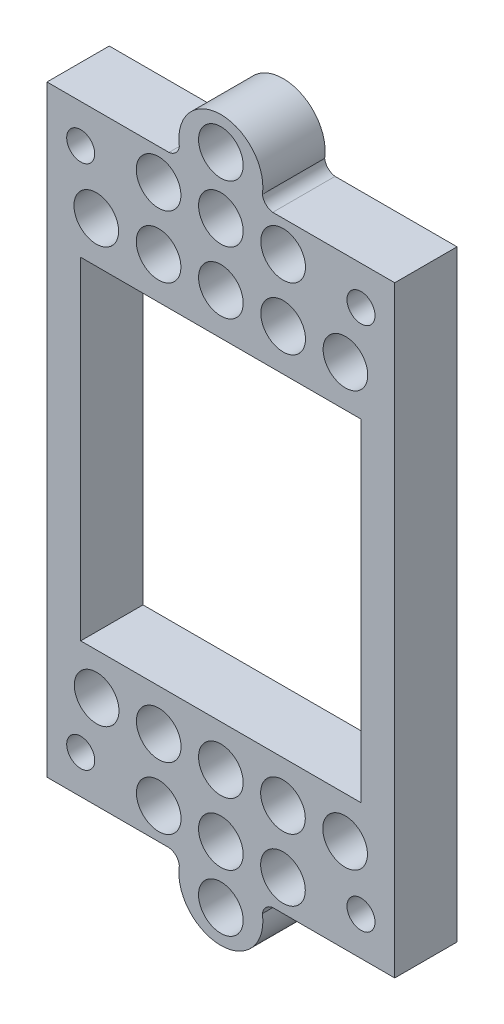
SolidWorks part; units mm, degrees
ref_plane "Front Plane" through (0, 0, 0) normal (0, 0, 1) x (1, 0, 0)
ref_plane "Top Plane" through (0, 0, 0) normal (0, 1, 0) x (1, 0, 0)
ref_plane "Right Plane" through (0, 0, 0) normal (1, 0, 0) x (0, 0, -1)
sketch "Sketch1" plane through (0, 0, 0) normal (0, 0, 1) x (1, 0, 0)
  line L0 (-13.5, -16) -> (13.5, -16)
  line L1 (-16.75, 29) -> (-5, 29)
  line L2 (-16.75, 29) -> (-16.75, -29)
  line L3 (-16.75, -29) -> (-5, -29)
  line L4 (16.75, 29) -> (16.75, -29)
  line L5 (-13.5, 16) -> (13.5, 16)
  line L6 (-13.5, 16) -> (-13.5, -16)
  line L8 (13.5, 16) -> (13.5, -16)
  line L14 (-19.5, 29.3) -> (19.5, 29.3) construction
  line L15 (-19.5, 29.3) -> (-19.5, -29.3) construction
  line L16 (-19.5, -29.3) -> (19.5, -29.3) construction
  line L17 (19.5, 29.3) -> (19.5, -29.3) construction
  line L18 (-4, 30) -> (4, 30) construction
  line L19 (-5, 27.5542) -> (5, 27.5542) construction
  line L20 (0, 0) -> (4.3335, 0) construction
  line L21 (5, 29) -> (16.75, 29)
  line L22 (5, -29) -> (16.75, -29)
  circle A2 centre (-13.5, 25.3) radius 1.35
  circle A4 centre (13.5, -25.3) radius 1.35
  circle A5 centre (-13.5, -25.3) radius 1.35
  circle A6 centre (13.5, 25.3) radius 1.35
  arc A7 (-4, 30) -> (4, 30) centre (0, 30.6158) cw
  circle A8 centre (0, 31.5) radius 2.15
  arc A9 (-4, 30) -> (-5, 29) centre (-5.1229, 30.1229) cw
  arc A10 (4, 30) -> (5, 29) centre (5.1511, 30.1511) ccw
  arc A11 (4, -30) -> (5, -29) centre (5.1511, -30.1511) cw
  arc A12 (-4, -30) -> (-5, -29) centre (-5.1229, -30.1229) ccw
  circle A13 centre (0, -31.5) radius 2.15
  arc A15 (-4, -30) -> (4, -30) centre (0, -30.6158) ccw
  point P10 (-16.75, 0)
  point P11 (0, 16)
  point P12 (-13.5, 0)
  point P29 (19.5, 0)
  point P30 (0, 29.3)
  point P39 (0, 30)
  point P46 (0, 27.5542)
  dimension "D8" = 2.7
  dimension "D22" = 4.3
  dimension "D23" = 2.5
  dimension "D1" = 27
  dimension "D2" = 33.5
  dimension "D3" = 58
  dimension "D4" = 32
  dimension "D9" = 58.6
  dimension "D10" = 39
  dimension "D11" = 6
  dimension "D12" = 4
  dimension "D13" = 4
  dimension "D14" = 6
  dimension "D15" = 6
  dimension "D16" = 6
  dimension "D17" = 4
  dimension "D18" = 4
  dimension "D19" = 8
  dimension "D20" = 1
  dimension "D21" = 10
extrude "Boss-Extrude1" add sketch "Sketch1" along normal blind 6
sketch "Sketch2" plane through (0, 0, 6) normal (0, 0, 1) x (1, 0, 0)
  line L3 (13.5, 16) -> (-13.5, 16) construction
  line L4 (-13.5, -16) -> (13.5, -16) construction
  circle A0 centre (-12, 20) radius 2.15
  circle A1 centre (-6, 20) radius 2.15
  circle A2 centre (0, 20) radius 2.15
  circle A3 centre (6, 20) radius 2.15
  circle A4 centre (12, 20) radius 2.15
  circle A5 centre (-6, 26) radius 2.15
  circle A6 centre (0, 26) radius 2.15
  circle A7 centre (6, 26) radius 2.15
  circle A8 centre (-11.9673, -20) radius 2.15
  circle A9 centre (-5.9837, -20) radius 2.15
  circle A10 centre (0, -20) radius 2.15
  circle A11 centre (5.9837, -20) radius 2.15
  circle A12 centre (11.9673, -20) radius 2.15
  circle A13 centre (-5.9837, -26) radius 2.15
  circle A14 centre (0, -26) radius 2.15
  circle A15 centre (5.9837, -26) radius 2.15
  point P28 (0, 0)
  point P29 (0, 0)
  point P34 (-0.75, 26)
  point P37 (5.25, 26)
  point P40 (-5.9837, -26)
  point P41 (5.9837, -26)
  point P42 (0, 0)
  point P44 (0, 0)
  point P45 (0, 0)
  point P46 (6, 26)
  dimension "D1" = 4.3
  dimension "D5" = 4.3
  dimension "D11" = 4.3
  dimension "D12" = 4.3
  dimension "D13" = 4.3
  dimension "D14" = 4.3
  dimension "D15" = 4.3
  dimension "D16" = 4.3
  dimension "D2" = 4
  dimension "D3" = 4
  dimension "D6" = 6
  dimension "D10" = 6
  dimension "D4" = 5
  dimension "D9" = 5
extrude "Cut-Extrude1" cut sketch "Sketch2" against normal blind 4.2
